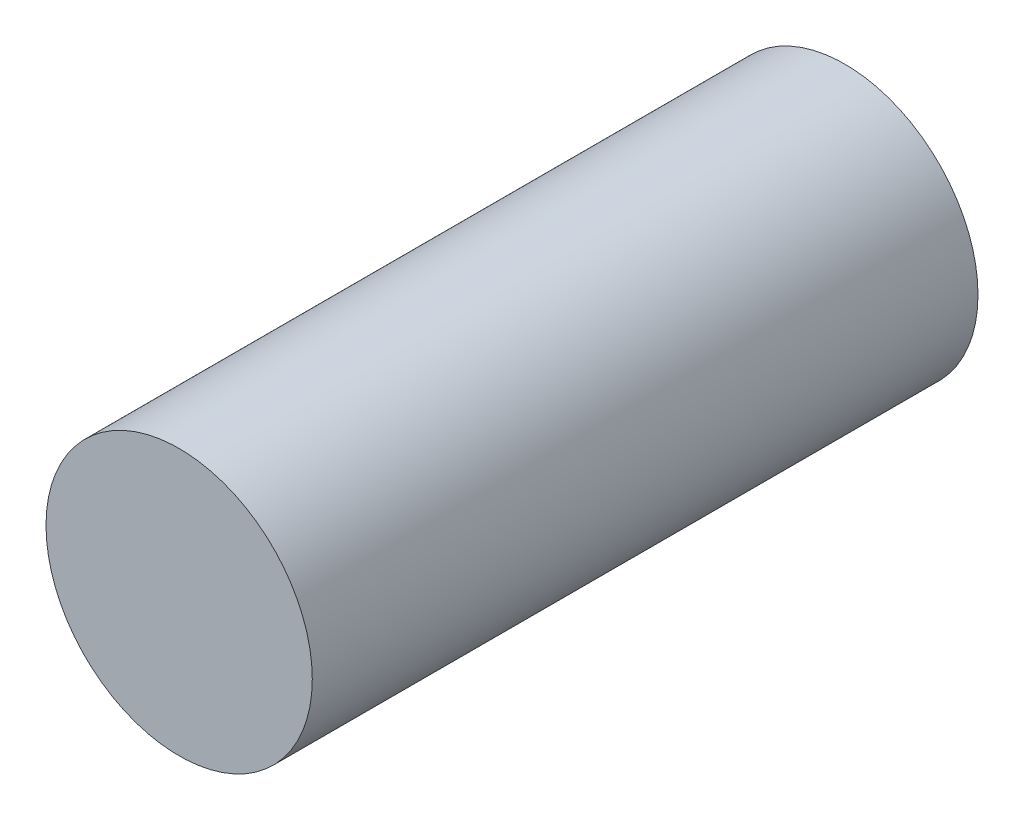
SolidWorks part; units mm, degrees
ref_plane "前视基准面" through (0, 0, 0) normal (0, 0, 1) x (1, 0, 0)
ref_plane "上视基准面" through (0, 0, 0) normal (0, 1, 0) x (1, 0, 0)
ref_plane "右视基准面" through (0, 0, 0) normal (1, 0, 0) x (0, 0, -1)
other "Configuration Table"
sketch "草图1" plane through (0, 0, 0) normal (0, 0, 1) x (1, 0, 0)
  circle A0 centre (0, 0) radius 3
  dimension "D1" = 6
extrude "凸台-拉伸1" add sketch "草图1" along normal blind 15
